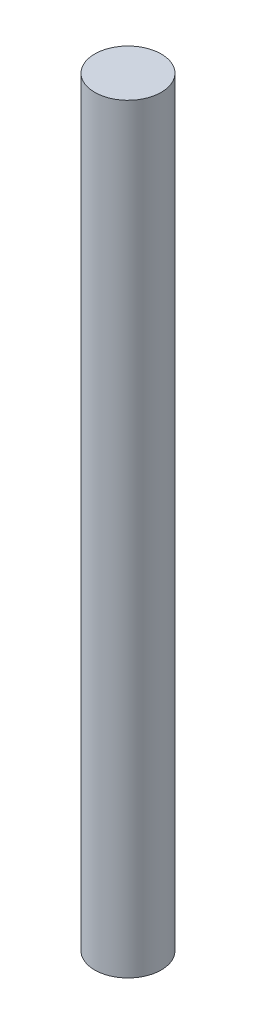
SolidWorks part; units mm, degrees
ref_plane "前视基准面" through (0, 0, 0) normal (0, 0, 1) x (1, 0, 0)
ref_plane "上视基准面" through (0, 0, 0) normal (0, 1, 0) x (1, 0, 0)
ref_plane "右视基准面" through (0, 0, 0) normal (1, 0, 0) x (0, 0, -1)
sketch "草图1" plane through (0, 0, 0) normal (0, 1, 0) x (1, 0, 0)
  circle A0 centre (0, 0) radius 1.75
  dimension "D1" = 3.5
extrude "凸台-拉伸1" add sketch "草图1" along normal blind 40
